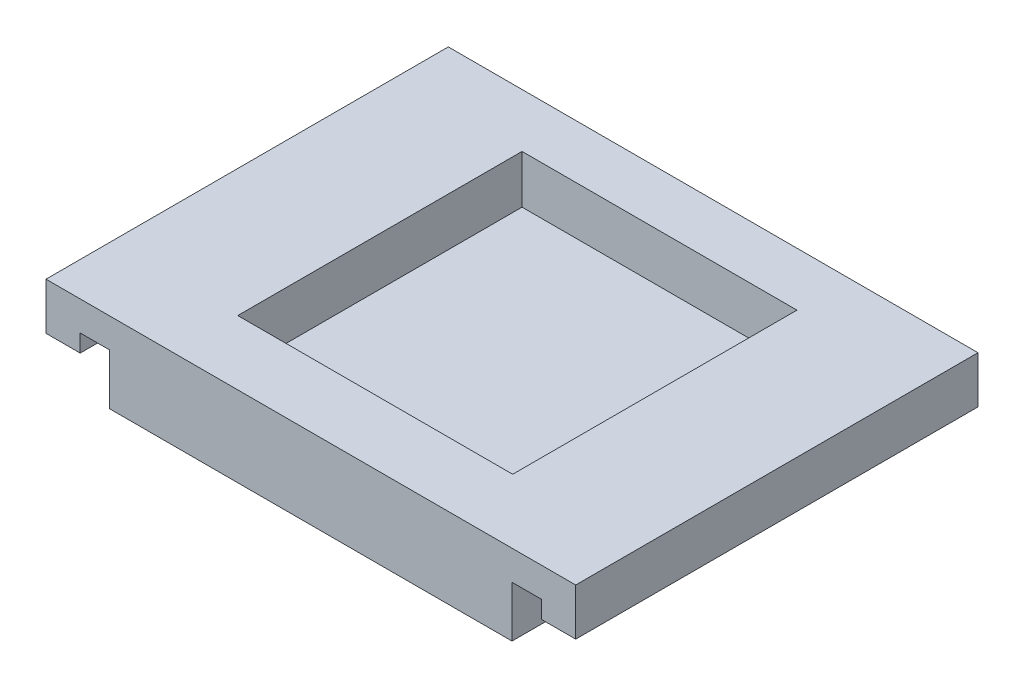
SolidWorks part; units mm, degrees
ref_plane "Front Plane" through (0, 0, 0) normal (0, 0, 1) x (1, 0, 0)
ref_plane "Top Plane" through (0, 0, 0) normal (0, 1, 0) x (1, 0, 0)
ref_plane "Right Plane" through (0, 0, 0) normal (1, 0, 0) x (0, 0, -1)
sketch "Sketch1" plane through (0, 0, 0) normal (0, 1, 0) x (1, 0, 0)
  line L1 (-15, -15) -> (15, -15)
  line L2 (-15, -15) -> (-15, 15)
  line L3 (-15, 15) -> (15, 15)
  line L4 (15, -15) -> (15, 15)
  line L5 (-15, -15) -> (15, 15) construction
  line L6 (-15, 15) -> (15, -15) construction
  point P0 (0, 0)
  dimension "D1" = 30
extrude "Main Body" add sketch "Sketch1" along normal blind 11
sketch "Sketch2" plane through (0, 0, 0) normal (0, -1, 0) x (1, 0, 0)
  line L0 (0, 15) -> (0, 8.6) construction
  line L1 (-15, 15) -> (15, 15) construction
  line L3 (-8.92, 7.2) -> (8.92, 7.2)
  line L4 (-8.92, 7.2) -> (-8.92, 10)
  line L5 (-8.92, 10) -> (8.92, 10)
  line L6 (8.92, 7.2) -> (8.92, 10)
  line L7 (-8.92, 7.2) -> (8.92, 10) construction
  line L8 (-8.92, 10) -> (8.92, 7.2) construction
  dimension "D1" = 6.4
  dimension "D2" = 2.8
  dimension "D3" = 17.84
extrude "Wire Hole" cut sketch "Sketch2" against normal blind 6 contours L4 L3 L6 L5
sketch "Sketch3" plane through (0, 0, 7.2) normal (0, 0, 1) x (1, 0, 0)
  line L0 (0, 0) -> (0, 4.2) construction
  line L2 (-10.25, 2.4) -> (10.25, 2.4)
  line L3 (-10.25, 2.4) -> (-10.25, 6)
  line L4 (-10.25, 6) -> (10.25, 6)
  line L5 (10.25, 2.4) -> (10.25, 6)
  line L6 (-10.25, 2.4) -> (10.25, 6) construction
  line L7 (-10.25, 6) -> (10.25, 2.4) construction
  dimension "D1" = 4.2
  dimension "D2" = 3.6
  dimension "D3" = 20.5
extrude "Board Cavity" cut sketch "Sketch3" against normal blind 17.2 and the other way blind 3
sketch "Sketch4" plane through (0, 6, 0) normal (0, -1, 0) x (1, 0, 0)
  line L0 (0, -10) -> (0, 0.05) construction
  line L1 (10.25, -10) -> (-10.25, -10) construction
  line L3 (-5, -4.95) -> (5, -4.95)
  line L4 (-5, -4.95) -> (-5, 5.05)
  line L5 (-5, 5.05) -> (5, 5.05)
  line L6 (5, -4.95) -> (5, 5.05)
  line L7 (-5, -4.95) -> (5, 5.05) construction
  line L8 (-5, 5.05) -> (5, -4.95) construction
  dimension "D1" = 10.05
  dimension "D2" = 10
extrude "Light Box" cut sketch "Sketch4" against normal blind 2
sketch "Sketch5" plane through (0, 8, 0) normal (0, -1, 0) x (1, 0, 0)
  line L0 (0, -4.95) -> (0, 0.05) construction
  line L1 (-5, -4.95) -> (5, -4.95) construction
  circle A0 centre (0, 0) radius 1.5
  dimension "D2" = 3
  dimension "D1" = 5
extrude "Cut-Extrude4" cut sketch "Sketch5" against normal blind 20
sketch "Sketch7" plane through (0, 0, -10) normal (0, 0, 1) x (1, 0, 0)
  line L0 (10.25, 2.4) -> (10.25, 6) construction
  line L5 (-10.25, 2.4) -> (10.25, 2.4)
  line L6 (-10.25, 2.4) -> (-10.25, 6)
  line L7 (-10.25, 6) -> (10.25, 6)
  line L8 (10.25, 2.4) -> (10.25, 6)
extrude "Cut-Extrude5" cut sketch "Sketch7" against normal blind 1
sketch "Sketch8" plane through (0, 0, -15) normal (0, 0, -1) x (-1, 0, 0)
  line L0 (-15, 5.5) -> (-15, 3.8)
  line L1 (-15, 11) -> (-15, 0) construction
  line L2 (-15, 3.8) -> (-17.2, 3.8)
  line L3 (-17.2, 3.8) -> (-17.2, 2.5)
  line L4 (-17.2, 2.5) -> (-19.75, 2.5)
  line L5 (-15, 5.5) -> (-15, 7.2)
  line L6 (-15, 7.2) -> (-17.2, 7.2)
  line L7 (-17.2, 7.2) -> (-17.2, 8.5)
  line L8 (-17.2, 8.5) -> (-19.75, 8.5)
  line L9 (-19.75, 8.5) -> (-19.75, 2.5)
  dimension "D1" = 1.7
  dimension "D2" = 2.2
  dimension "D3" = 1.3
  dimension "D4" = 2.55
  dimension "D5" = 1.7
  dimension "D6" = 2.2
  dimension "D7" = 1.3
  dimension "D8" = 2.55
extrude "Boss-Extrude1" add sketch "Sketch8" against normal blind 30
mirror "Mirror1" about plane through (0, 0, 0) normal (1, 0, 0) of "Boss-Extrude1"
sketch "Sketch9" plane through (0, 0, 0) normal (0, 0, 1) x (1, 0, 0)
  line L0 (5, 8) -> (-5, 8) construction
  line L1 (-1.5, 8) -> (1.5, 8) construction
  line L2 (0, 67.9718) -> (0, 8)
  line L3 (-1.3, 8) -> (0, 8)
  arc A0 (0, 67.9718) -> (-1.3, 8) centre (0, 37.9718) ccw
  dimension "D1" = 30
sketch "Sketch10" plane through (0, 0, 0) normal (0, 0, 1) x (1, 0, 0)
  line L0 (0, 0) -> (0, -5) construction
  dimension "D1" = 5
revolve "Cut-Revolve6" cut sketch "Sketch9" angle 360 about L0
sketch "Sketch11" plane through (0, 8, 0) normal (0, -1, 0) x (1, 0, 0)
  line L1 (-5, 5.05) -> (5, 5.05)
  line L2 (-5, 5.05) -> (-5, -4.95)
  line L3 (-5, -4.95) -> (5, -4.95)
  line L4 (5, 5.05) -> (5, -4.95)
  circle A0 centre (0, 0) radius 1.5
extrude "Boss-Extrude2" add sketch "Sketch11" along normal blind 0.6
sketch "Sketch12" plane through (0, 0, -15) normal (0, 0, -1) x (-1, 0, 0)
  line L0 (-24.5354, 0) -> (-24.5354, 6) construction
  line L2 (-24.5354, 6) -> (20.2792, 6)
  line L3 (-24.5354, 6) -> (-24.5354, 13.5778)
  line L4 (-24.5354, 13.5778) -> (20.2792, 13.5778)
  line L5 (20.2792, 6) -> (20.2792, 13.5778)
  dimension "D1" = 6
extrude "Cut-Extrude6" cut sketch "Sketch12" against normal blind 40
